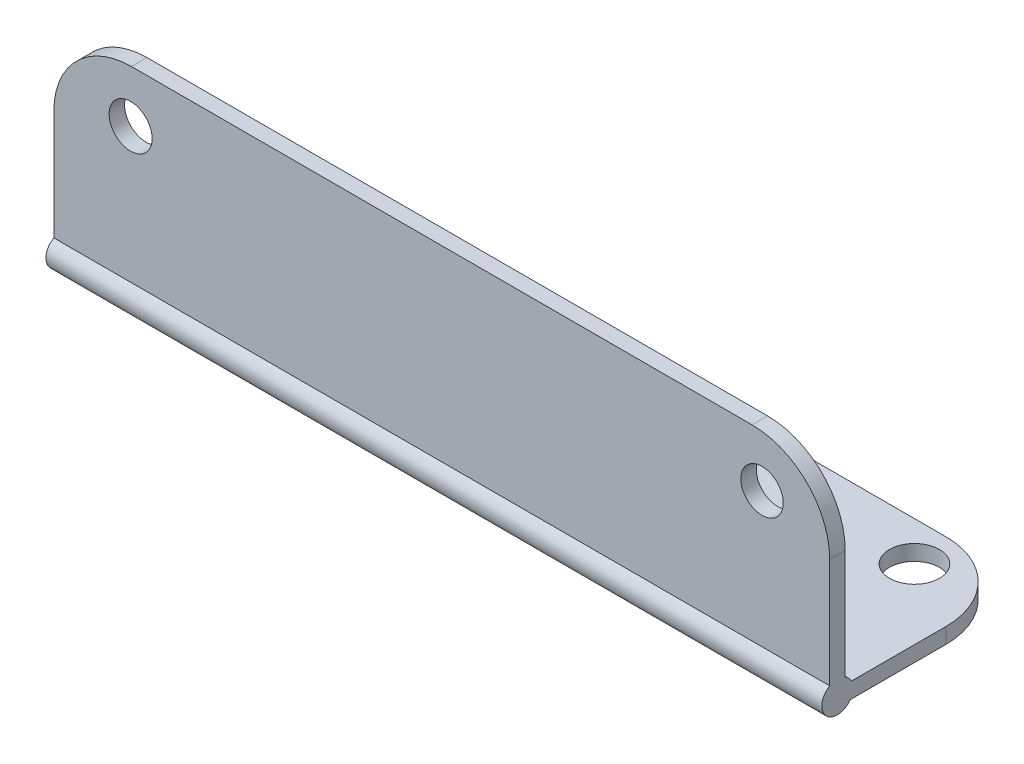
SolidWorks part; units mm, degrees
ref_plane "Front Plane" through (0, 0, 0) normal (0, 0, 1) x (1, 0, 0)
ref_plane "Top Plane" through (0, 0, 0) normal (0, 1, 0) x (1, 0, 0)
ref_plane "Right Plane" through (0, 0, 0) normal (1, 0, 0) x (0, 0, -1)
sketch "Sketch1" plane through (0, 0, 0) normal (0, 0, 1) x (1, 0, 0)
  line L1 (2.54, 0) -> (22.86, 0)
  line L2 (0, -2.54) -> (0, -6.35)
  line L3 (0, -6.35) -> (25.4, -6.35)
  line L4 (25.4, -2.54) -> (25.4, -6.35)
  line L5 (0, 0) -> (25.4, -6.35) construction
  line L6 (0, -6.35) -> (25.4, 0) construction
  arc A0 (25.4, -2.54) -> (22.86, 0) centre (22.86, -2.54) ccw
  arc A1 (0, -2.54) -> (2.54, 0) centre (2.54, -2.54) cw
  point P4 (12.7, -3.175)
  dimension "D1" = 2.54
  dimension "D2" = 6.35
  dimension "D3" = 25.4
extrude "Boss-Extrude1" add sketch "Sketch1" along normal blind 0.508
sketch "Sketch2" plane through (0, -6.35, 0) normal (0, -1, 0) x (1, 0, 0)
  line L1 (25.4, 0.508) -> (0, 0.508)
  line L2 (25.4, 0.508) -> (25.4, -3.302)
  line L3 (22.86, -5.842) -> (2.54, -5.842)
  line L4 (0, 0.508) -> (0, -3.302)
  line L5 (25.4, 0.508) -> (0, -5.842) construction
  line L6 (25.4, -5.842) -> (0, 0.508) construction
  arc A0 (25.4, -3.302) -> (22.86, -5.842) centre (22.86, -3.302) cw
  arc A1 (2.54, -5.842) -> (0, -3.302) centre (2.54, -3.302) cw
  point P4 (12.7, -2.667)
  dimension "D3" = 2.54
  dimension "D1" = 25.4
  dimension "D2" = 6.35
extrude "Boss-Extrude2" add sketch "Sketch2" along normal blind 0.508
sketch "Sketch3" plane through (25.4, 0, 0) normal (1, 0, 0) x (0, 0, -1)
  circle A0 centre (-0.2572, -6.5712) radius 0.508
extrude "Boss-Extrude3" add sketch "Sketch3" against normal blind 25.4
sketch "Sketch4" plane through (0, 0, 0) normal (0, 0, -1) x (-1, 0, 0)
  circle A0 centre (-23.1848, -1.7085) radius 0.6948
  circle A1 centre (-2.5136, -1.7085) radius 0.7053
extrude "Cut-Extrude1" cut sketch "Sketch4" against normal blind 25.4
sketch "Sketch5" plane through (0, -6.35, 0) normal (0, 1, 0) x (1, 0, 0)
  circle A0 centre (2.5718, 3.7847) radius 0.7731
  circle A1 centre (23.109, 4.5578) radius 0.8184
extrude "Cut-Extrude2" cut sketch "Sketch5" against normal blind 25.4
